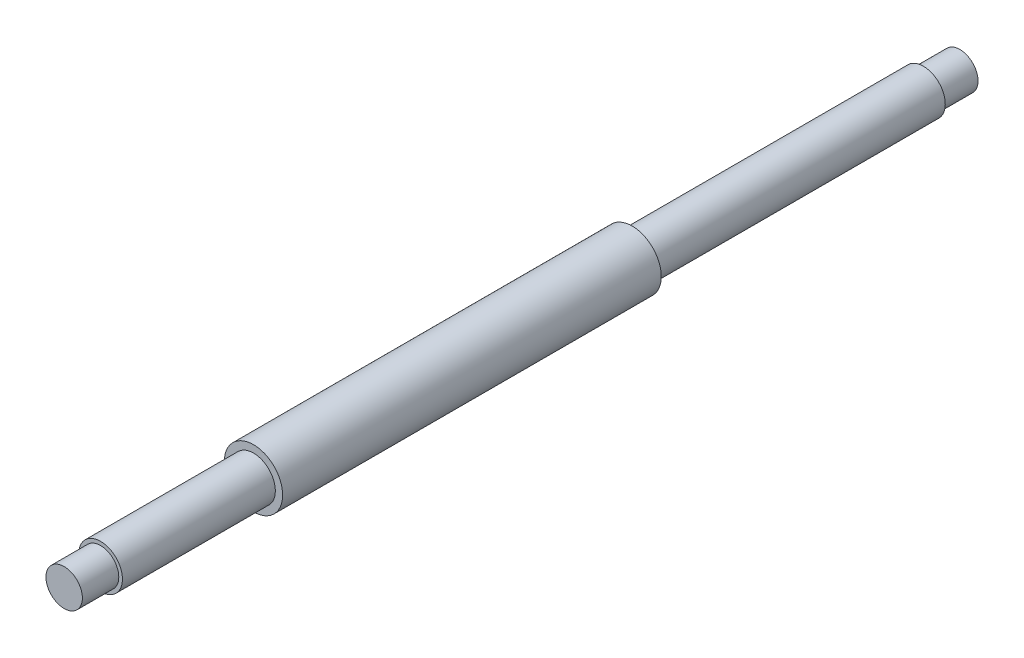
SolidWorks part; units mm, degrees
ref_plane "前视基准面" through (0, 0, 0) normal (0, 0, 1) x (1, 0, 0)
ref_plane "上视基准面" through (0, 0, 0) normal (0, 1, 0) x (1, 0, 0)
ref_plane "右视基准面" through (0, 0, 0) normal (1, 0, 0) x (0, 0, -1)
other "Configuration Table"
sketch "草图1" plane through (0, 0, 0) normal (0, 0, 1) x (1, 0, 0)
  circle A0 centre (0, 0) radius 4
  dimension "D1" = 8
extrude "凸台-拉伸1" add sketch "草图1" along normal blind 52
sketch "草图2" plane through (0, 0, 52) normal (0, 0, 1) x (1, 0, 0)
  circle A0 centre (0, 0) radius 3
  dimension "D1" = 6
extrude "凸台-拉伸2" add sketch "草图2" along normal blind 21 and the other way blind 92
sketch "草图3" plane through (0, 0, -40) normal (0, 0, -1) x (-1, 0, 0)
  circle A0 centre (0, 0) radius 2.5
  dimension "D1" = 5
extrude "凸台-拉伸3" add sketch "草图3" along normal blind 5
sketch "草图4" plane through (0, 0, 73) normal (0, 0, 1) x (1, 0, 0)
  circle A0 centre (0, 0) radius 2.5
  dimension "D1" = 5
extrude "凸台-拉伸4" add sketch "草图4" along normal blind 5
